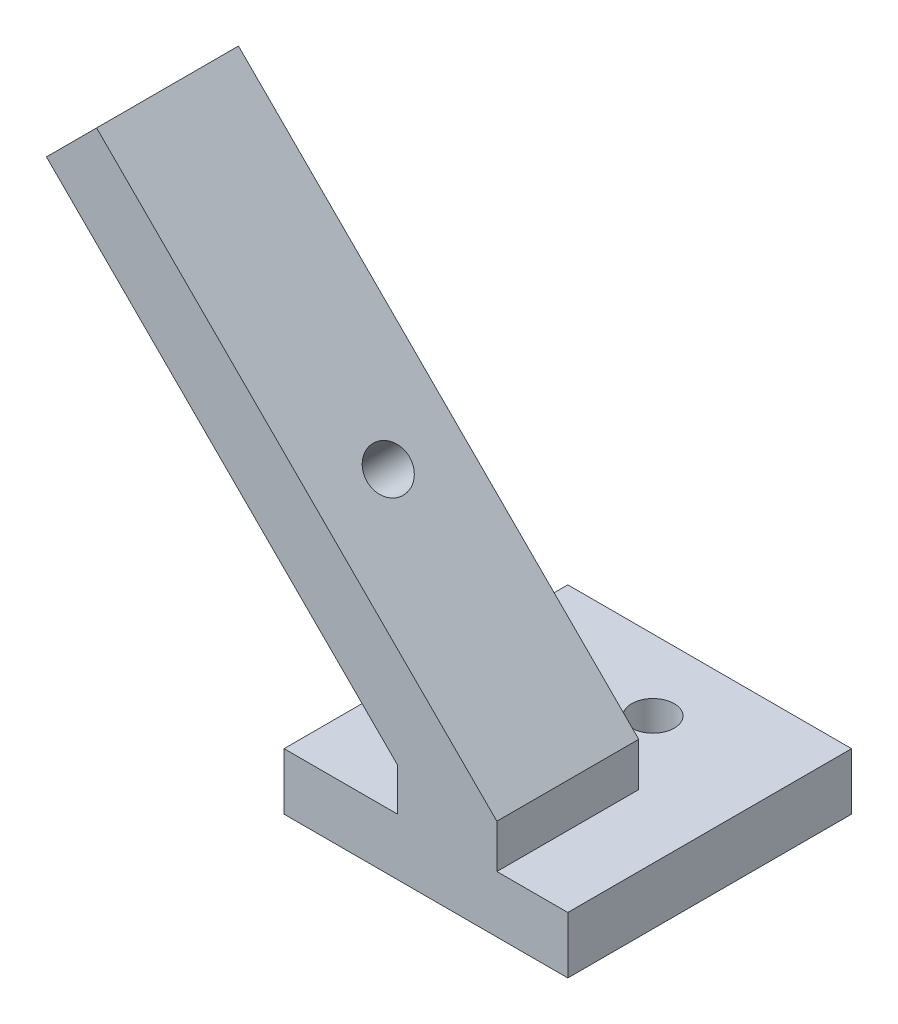
SolidWorks part; units mm, degrees
ref_plane "前视基准面" through (0, 0, 0) normal (0, 0, 1) x (1, 0, 0)
ref_plane "上视基准面" through (0, 0, 0) normal (0, 1, 0) x (1, 0, 0)
ref_plane "右视基准面" through (0, 0, 0) normal (1, 0, 0) x (0, 0, -1)
sketch "草图1" plane through (0, 0, 0) normal (0, 0, 1) x (1, 0, 0)
  line L0 (0, 0) -> (12, 0)
  line L1 (12, 0) -> (12, 4)
  line L2 (12, 4) -> (7, 4)
  line L6 (7, 4) -> (7, 7.0711)
  line L7 (7, 7.0711) -> (-21.2132, 35.2843)
  line L8 (-21.2132, 35.2843) -> (-24.7487, 31.7487)
  line L9 (-24.7487, 31.7487) -> (0, 7)
  line L10 (0, 7) -> (0, 0)
  dimension "D1" = 135
  dimension "D2" = 4
  dimension "D3" = 5
  dimension "D4" = 35
  dimension "D5" = 7
  dimension "D6" = 12
  dimension "D7" = 7
extrude "凸台-拉伸1" add sketch "草图1" along normal blind 10
sketch "草图2" plane through (0, 0, 0) normal (0, 0, -1) x (-1, 0, 0)
  line L1 (-12, 4) -> (8, 4)
  line L2 (-12, 4) -> (-12, 0)
  line L3 (-12, 0) -> (8, 0)
  line L4 (8, 4) -> (8, 0)
  dimension "D1" = 20
  dimension "D2" = 4
extrude "凸台-拉伸2" add sketch "草图2" along normal blind 10 and the other way through all
sketch "草图3" plane through (7.0355, 7.0355, 0) normal (0.7071, 0.7071, 0) x (0, 0, -1)
  line L0 (0, 0.0503) -> (0, 39.9497) construction
  line L1 (-10, 39.9497) -> (0, 39.9497) construction
  circle A0 centre (-5, 17.9497) radius 1.5
  dimension "D3" = 3
  dimension "D1" = 5
  dimension "D2" = 22
extrude "切除-拉伸1" cut sketch "草图3" against normal blind 10
sketch "草图4" plane through (0, 4, 0) normal (0, 1, 0) x (1, 0, 0)
  line L0 (-8, -10) -> (-8, 10) construction
  line L2 (-8, 10) -> (12, 10) construction
  circle A0 centre (-5, 5) radius 1.5
  circle A1 centre (3, 5) radius 1.5
  dimension "D4" = 3
  dimension "D1" = 3
  dimension "D2" = 8
  dimension "D3" = 5
extrude "切除-拉伸2" cut sketch "草图4" against normal blind 10
